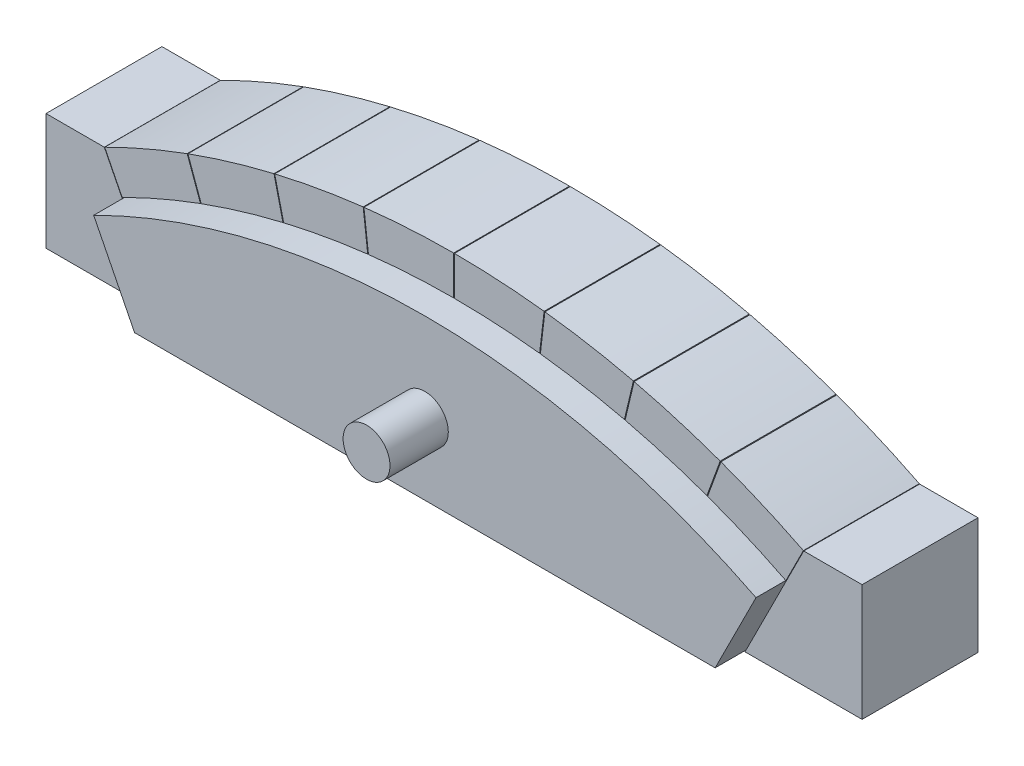
SolidWorks part; units mm, degrees
ref_plane "Front Plane" through (0, 0, 0) normal (0, 0, 1) x (1, 0, 0)
ref_plane "Top Plane" through (0, 0, 0) normal (0, 1, 0) x (1, 0, 0)
ref_plane "Right Plane" through (0, 0, 0) normal (1, 0, 0) x (0, 0, -1)
sketch "Sketch1" plane through (0, 0, 0) normal (0, 0, 1) x (1, 0, 0)
  line L0 (0, 0) -> (209.8, 0) construction
  line L1 (0, 0) -> (0, 30)
  line L2 (0, 30) -> (15, 30)
  line L3 (15, 30) -> (30.096, 0)
  line L4 (30.096, 0) -> (0, 0)
  line L5 (104.9, 0) -> (104.9, -148.6561) construction
  line L6 (179.704, 0) -> (209.8, 0)
  line L7 (194.8, 30) -> (179.704, 0)
  line L8 (209.8, 30) -> (194.8, 30)
  line L9 (209.8, 0) -> (209.8, 30)
  line L10 (104.9, -148.6561) -> (25.558, 34.9327) construction
  line L11 (15.0893, 30.0449) -> (19.5843, 21.1121)
  line L12 (36.2915, 39.2079) -> (39.7172, 29.813)
  line L13 (36.4794, 39.2764) -> (39.9051, 29.8815)
  line L14 (58.6032, 45.9117) -> (60.9132, 36.1821)
  line L15 (58.7978, 45.9579) -> (61.1078, 36.2283)
  line L16 (81.5431, 49.9754) -> (82.706, 40.0432)
  line L17 (81.7418, 49.9987) -> (82.9047, 40.0665)
  line L18 (104.8, 51.3439) -> (104.8, 41.3439)
  line L19 (105, 51.3439) -> (105, 41.3439)
  line L20 (128.0582, 49.9987) -> (126.8953, 40.0665)
  line L21 (128.2569, 49.9754) -> (127.094, 40.0432)
  line L22 (151.0022, 45.9579) -> (148.6922, 36.2283)
  line L23 (151.1968, 45.9117) -> (148.8868, 36.1821)
  line L24 (173.3206, 39.2764) -> (169.8949, 29.8815)
  line L25 (173.5085, 39.2079) -> (170.0828, 29.813)
  line L26 (194.7107, 30.0449) -> (190.2157, 21.1121)
  arc A0 (15, 30) -> (194.8, 30) centre (104.9, -148.6561) cw construction
  arc A1 (36.2915, 39.2079) -> (15.0893, 30.0449) centre (104.9, -148.6561) ccw
  arc A2 (19.5843, 21.1121) -> (39.7172, 29.813) centre (104.9, -148.6561) cw
  arc A3 (39.9051, 29.8815) -> (60.9132, 36.1821) centre (104.9, -148.6561) cw
  arc A4 (58.6032, 45.9117) -> (36.4794, 39.2764) centre (104.9, -148.6561) ccw
  arc A5 (61.1078, 36.2283) -> (82.706, 40.0432) centre (104.9, -148.6561) cw
  arc A6 (81.5431, 49.9754) -> (58.7978, 45.9579) centre (104.9, -148.6561) ccw
  arc A7 (82.9047, 40.0665) -> (104.8, 41.3439) centre (104.9, -148.6561) cw
  arc A8 (104.8, 51.3439) -> (81.7418, 49.9987) centre (104.9, -148.6561) ccw
  arc A9 (105, 41.3439) -> (126.8953, 40.0665) centre (104.9, -148.6561) cw
  arc A10 (128.0582, 49.9987) -> (105, 51.3439) centre (104.9, -148.6561) ccw
  arc A11 (127.094, 40.0432) -> (148.6922, 36.2283) centre (104.9, -148.6561) cw
  arc A12 (151.0022, 45.9579) -> (128.2569, 49.9754) centre (104.9, -148.6561) ccw
  arc A13 (148.8868, 36.1821) -> (169.8949, 29.8815) centre (104.9, -148.6561) cw
  arc A14 (173.3206, 39.2764) -> (151.1968, 45.9117) centre (104.9, -148.6561) ccw
  arc A15 (170.0828, 29.813) -> (190.2157, 21.1121) centre (104.9, -148.6561) cw
  arc A16 (194.7107, 30.0449) -> (173.5085, 39.2079) centre (104.9, -148.6561) ccw
  dimension "D4" = 200
  dimension "D1" = 209.8
  dimension "D2" = 15
  dimension "D3" = 30
  dimension "D5" = 0.1
  dimension "D6" = 8
  dimension "D7" = 10
extrude "Boss-Extrude1" add sketch "Sketch1" along normal blind 29.8
sketch "Sketch2" plane through (0, 0, 29.8) normal (0, 0, 1) x (1, 0, 0)
  line L2 (30.2747, 0.0899) -> (15.1787, 30.0899)
  line L3 (30.2747, 0.0899) -> (19.7636, 20.9783)
  line L4 (30.2747, 0.0899) -> (179.5253, 0.0899)
  line L5 (194.6213, 30.0899) -> (179.5253, 0.0899)
  line L6 (190.0364, 20.9783) -> (179.5253, 0.0899)
  arc A7 (39.7858, 29.6251) -> (19.6741, 20.9334) centre (104.9, -148.6561) ccw
  arc A8 (190.0364, 20.9783) -> (19.7636, 20.9783) centre (104.9, -148.6561) ccw
  dimension "D1" = 0.2
  dimension "D2" = 0.2
  dimension "D3" = 0.2
extrude "Boss-Extrude2" add sketch "Sketch2" along normal mid plane 15 separate body
sketch "Sketch3" plane through (0, 0, 37.3) normal (0, 0, 1) x (1, 0, 0)
  line L0 (104.9, 0.0899) -> (104.9, 18.3064) construction
  line L1 (30.2747, 0.0899) -> (179.5253, 0.0899) construction
  circle A0 centre (104.9, 18.3064) radius 6.0271
extrude "Boss-Extrude3" add sketch "Sketch3" along normal blind 15
